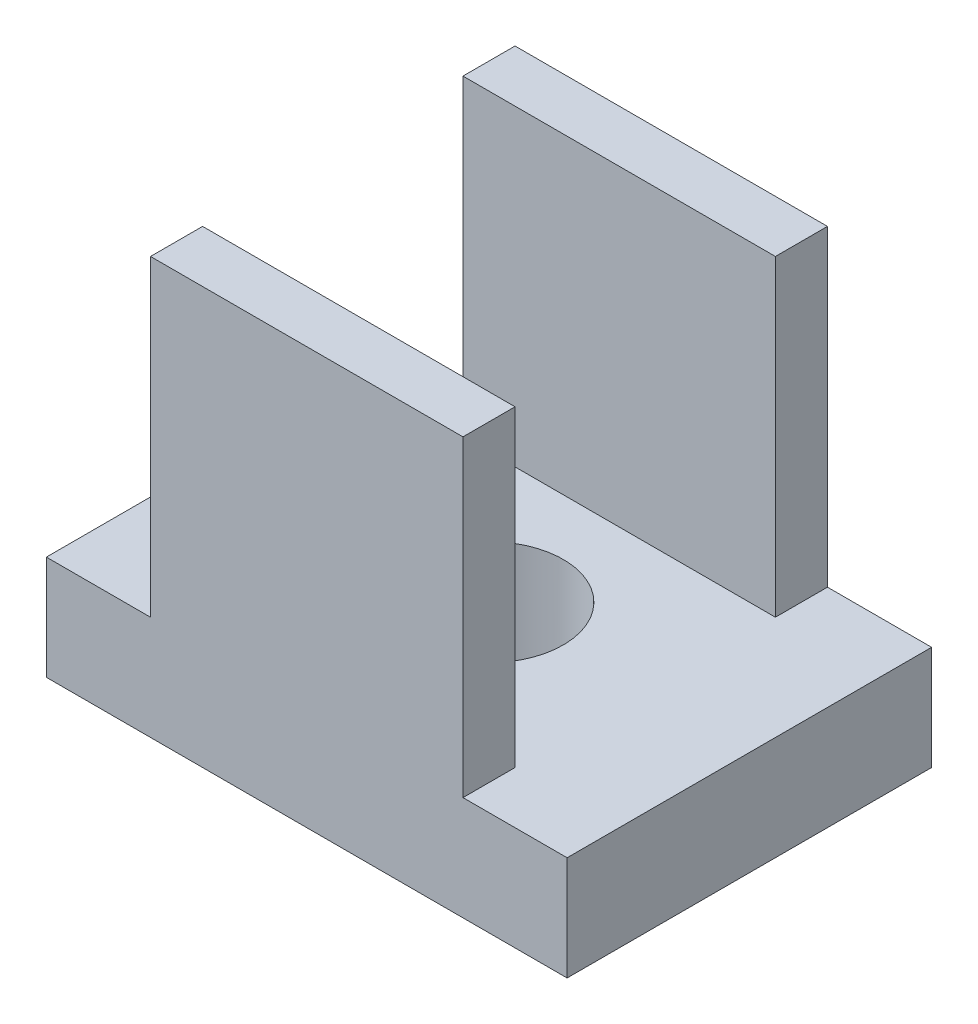
SolidWorks part; units mm, degrees
ref_plane "Front Plane" through (0, 0, 0) normal (0, 0, 1) x (1, 0, 0)
ref_plane "Top Plane" through (0, 0, 0) normal (0, 1, 0) x (1, 0, 0)
ref_plane "Right Plane" through (0, 0, 0) normal (1, 0, 0) x (0, 0, -1)
sketch "Sketch1" plane through (0, 0, 0) normal (0, 1, 0) x (1, 0, 0)
  line L1 (-5, -3.5) -> (5, -3.5)
  line L2 (-5, -3.5) -> (-5, 3.5)
  line L3 (-5, 3.5) -> (5, 3.5)
  line L4 (5, -3.5) -> (5, 3.5)
  line L5 (-5, -3.5) -> (5, 3.5) construction
  line L6 (-5, 3.5) -> (5, -3.5) construction
  point P0 (0, 0)
  dimension "D1" = 10
  dimension "D2" = 7
extrude "Boss-Extrude1" add sketch "Sketch1" along normal blind 2
sketch "Sketch2" plane through (0, 2, 0) normal (0, 1, 0) x (1, 0, 0)
  circle A0 centre (0, 0) radius 1.425
  dimension "D1" = 2.85
extrude "Cut-Extrude1" cut sketch "Sketch2" against normal blind 15
sketch "Sketch4" plane through (0, 2, 0) normal (0, 1, 0) x (1, 0, 0)
  line L0 (0, 0) -> (2.2111, 0) construction
  line L1 (-3, 3.5) -> (3, 3.5)
  line L2 (5, 3.5) -> (-5, 3.5) construction
  line L3 (0, 0) -> (0, 0.5179) construction
  line L4 (3, 3.5) -> (3, 2.5)
  line L5 (3, 2.5) -> (-3, 2.5)
  line L6 (-3, 3.5) -> (-3, 2.5)
  line L7 (-3, -3.5) -> (-3, -2.5)
  line L8 (3, -2.5) -> (-3, -2.5)
  line L9 (3, -3.5) -> (3, -2.5)
  line L10 (-3, -3.5) -> (3, -3.5)
  point P11 (0, 2.5)
  point P12 (0, 3.5)
  point P16 (0, -3.5)
  point P17 (0, -2.5)
  dimension "D1" = 3
  dimension "D2" = 1
extrude "Boss-Extrude2" add sketch "Sketch4" along normal blind 6
